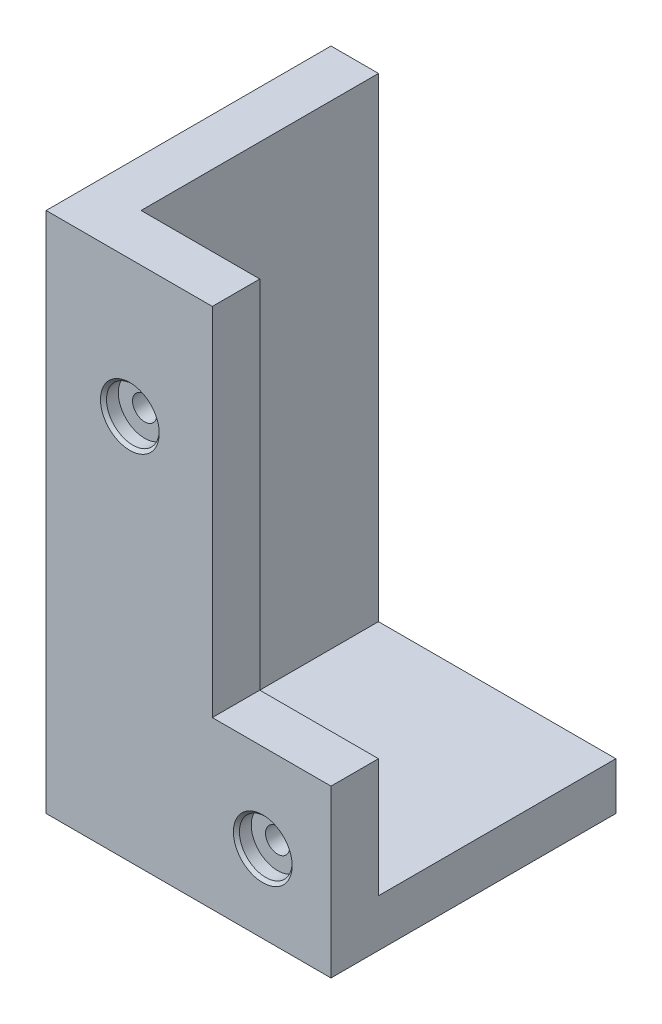
SolidWorks part; units mm, degrees
ref_plane "Front Plane" through (0, 0, 0) normal (0, 0, 1) x (1, 0, 0)
ref_plane "Top Plane" through (0, 0, 0) normal (0, 1, 0) x (1, 0, 0)
ref_plane "Right Plane" through (0, 0, 0) normal (1, 0, 0) x (0, 0, -1)
sketch "Sketch1" plane through (0, 0, 0) normal (0, 0, 1) x (1, 0, 0)
  line L0 (0, 110) -> (10, 110)
  line L1 (0, 0) -> (60, 0)
  line L2 (0, 0) -> (0, 110)
  line L3 (60, 10) -> (60, 0)
  line L5 (10, 110) -> (10, 10)
  line L6 (10, 10) -> (60, 10)
  dimension "D1" = 110
extrude "Boss-Extrude1" add sketch "Sketch1" along normal blind 50
sketch "Sketch2" plane through (0, 0, 50) normal (0, 0, 1) x (1, 0, 0)
  line L0 (0, 110) -> (35, 110)
  line L1 (0, 110) -> (0, 0) construction
  line L2 (10, 110) -> (0, 110) construction
  line L3 (35, 110) -> (35, 35)
  line L4 (35, 35) -> (60, 35)
  line L5 (60, 35) -> (60, 0)
  line L6 (60, 0) -> (60, 10) construction
  line L7 (60, 0) -> (0, 0)
  line L8 (0, 0) -> (0, 110)
  dimension "D1" = 35
  dimension "D2" = 35
extrude "Boss-Extrude2" add sketch "Sketch2" along normal blind 10
hole_wizard "CBORE for #10 Binding Head Machine Screw1" positions "Sketch4" profile "Sketch3" counterbore size "#10" standard "ANSI Inch" end condition through all
sketch "Sketch4" plane through (0, 0, 60) normal (0, 0, 1) x (1, 0, 0)
  point P0 (17.6352, 81.2462)
  point P2 (45.6311, 16.389)
sketch "Sketch3" plane through (17.6352, 81.2462, 60) normal (1, 0, 0) x (0, -1, 0)
  line L0 (0, 0) -> (0, 60)
  line L1 (0, 60) -> (2.5527, 60)
  line L3 (2.5527, 60) -> (2.5527, 3.1242)
  line L4 (5.5562, 3.1242) -> (2.5527, 3.1242)
  line L5 (5.5562, 3.1242) -> (5.5563, 0.635)
  line L6 (5.5563, 0.635) -> (6.1912, 0)
  line L7 (6.1912, 0) -> (0, 0)
  line L8 (-5.5563, 0.635) -> (-6.1912, 0) construction
  line L11 (0, -6.35) -> (0, 107.95) construction
  dimension "Thru Hole Dia." = 5.1054
  dimension "Thru Hole Depth" = 60
  dimension "C'Bore Dia." = 11.1125
  dimension "C'Bore Depth" = 3.1242
  dimension "Near C'Sink Dia." = 12.3825
  dimension "Near C'Sink Angle" = 90
